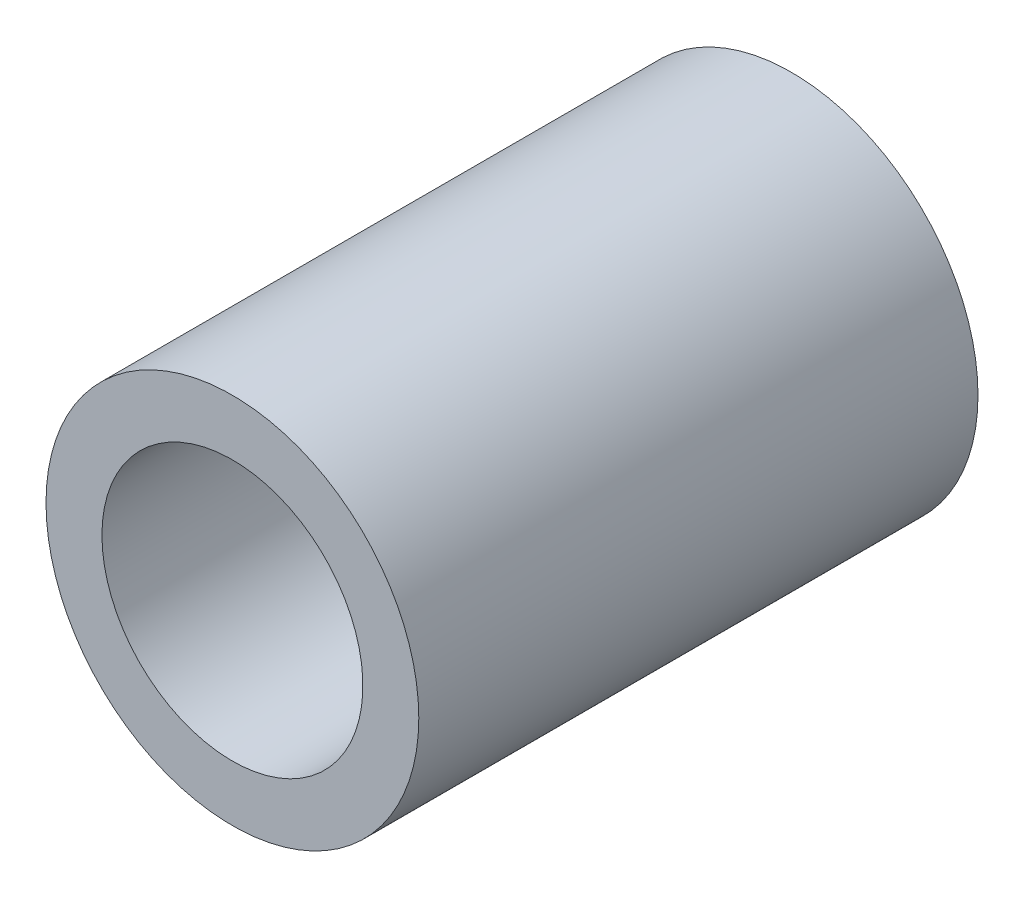
SolidWorks part; units mm, degrees
ref_plane "Front Plane" through (0, 0, 0) normal (0, 0, 1) x (1, 0, 0)
ref_plane "Top Plane" through (0, 0, 0) normal (0, 1, 0) x (1, 0, 0)
ref_plane "Right Plane" through (0, 0, 0) normal (1, 0, 0) x (0, 0, -1)
sketch "Sketch1" plane through (0, 0, 0) normal (0, 0, 1) x (1, 0, 0)
  circle A0 centre (0, 0) radius 1.4
  dimension "D1" = 2.8
extrude "Boss-Extrude1" add sketch "Sketch1" along normal blind 6
sketch "Sketch2" plane through (0, 0, 0) normal (0, 0, -1) x (-1, 0, 0)
  circle A0 centre (0, 0) radius 2
  dimension "D1" = 4
extrude "Boss-Extrude2" add sketch "Sketch2" along normal blind 6
sketch "Sketch3" plane through (0, 0, -6) normal (0, 0, -1) x (-1, 0, 0)
  circle A0 centre (0, 0) radius 1.4
  dimension "D1" = 2.8
extrude "Cut-Extrude1" cut sketch "Sketch3" against normal through all
